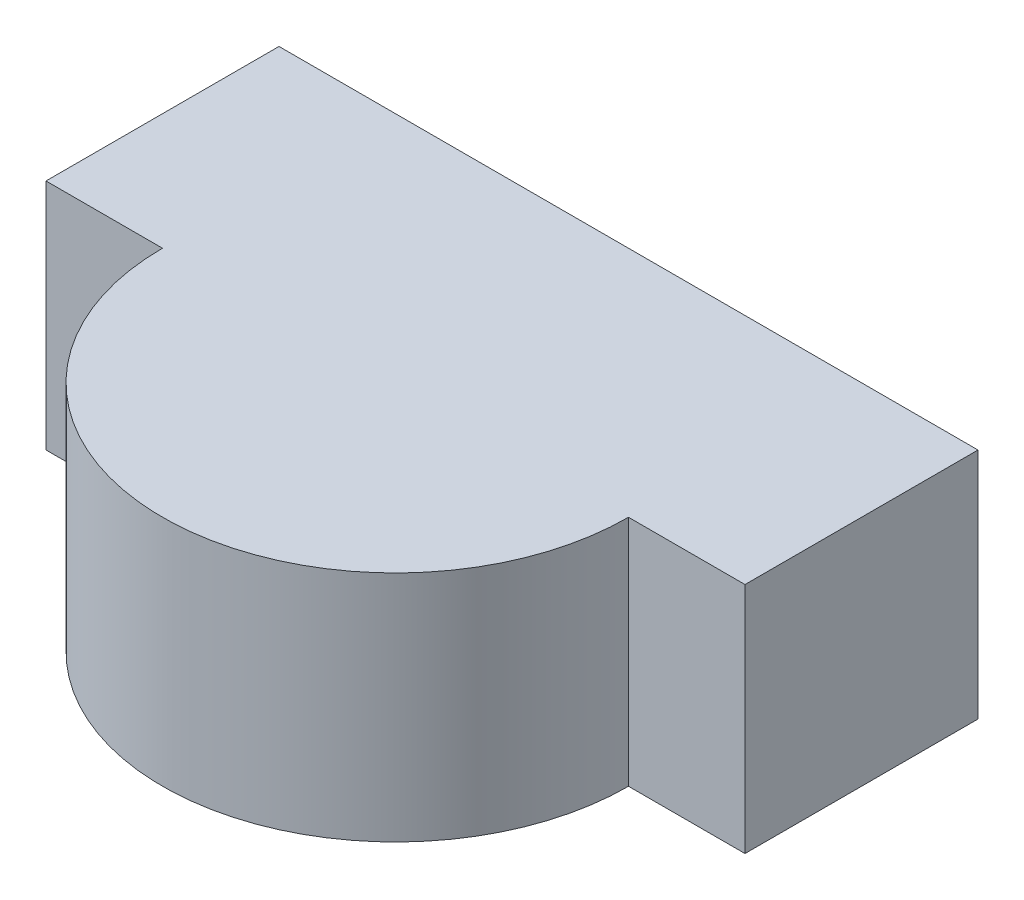
SolidWorks part; units mm, degrees
ref_plane "Front Plane" through (0, 0, 0) normal (0, 0, 1) x (1, 0, 0)
ref_plane "Top Plane" through (0, 0, 0) normal (0, 1, 0) x (1, 0, 0)
ref_plane "Right Plane" through (0, 0, 0) normal (1, 0, 0) x (0, 0, -1)
sketch "Sketch1" plane through (0, 0, 0) normal (0, 1, 0) x (1, 0, 0)
  line L0 (-1.5, 0.5) -> (1.5, 0.5)
  line L1 (1, -0.5) -> (1.5, -0.5)
  line L2 (-1.5, 0.5) -> (-1.5, -0.5)
  line L3 (-1.5, -0.5) -> (-1, -0.5)
  line L4 (1.5, 0.5) -> (1.5, -0.5)
  line L5 (-1.5, 0.5) -> (1.5, -0.5) construction
  line L6 (-1.5, -0.5) -> (1.5, 0.5) construction
  arc A0 (-1, -0.5) -> (1, -0.5) centre (0, -0.5) ccw
  point P0 (0, 0)
  dimension "D3" = 1
  dimension "D1" = 3
  dimension "D2" = 1
  dimension "D4" = 0.5
  dimension "D5" = 0.5
extrude "Boss-Extrude1" add sketch "Sketch1" along normal blind 1
